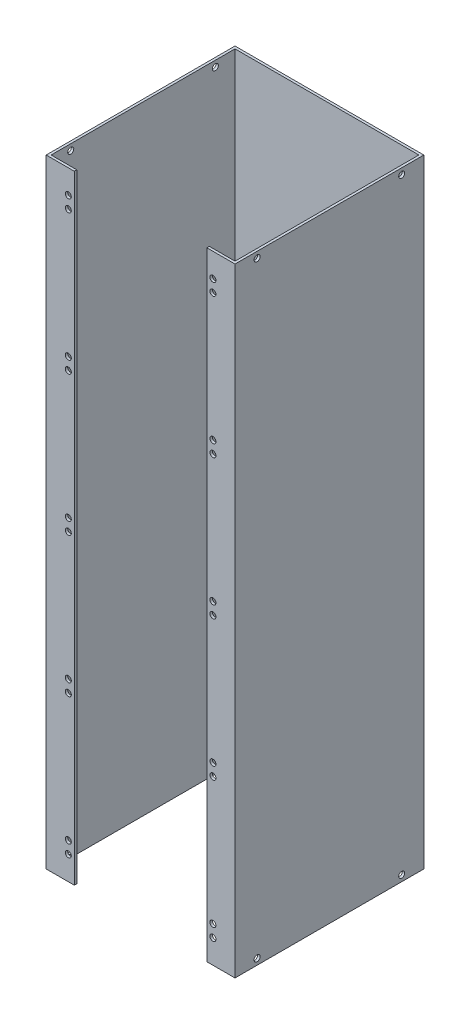
SolidWorks part; units mm, degrees
ref_plane "Front Plane" through (0, 0, 0) normal (0, 0, 1) x (1, 0, 0)
ref_plane "Top Plane" through (0, 0, 0) normal (0, 1, 0) x (1, 0, 0)
ref_plane "Right Plane" through (0, 0, 0) normal (1, 0, 0) x (0, 0, -1)
sketch "Sketch1" plane through (0, 0, 0) normal (0, 1, 0) x (1, 0, 0)
  line L0 (0, 0) -> (14.9, 0)
  line L1 (14.9, 0) -> (14.9, 1.3)
  line L2 (14.9, 1.3) -> (1.3, 1.3)
  line L3 (1.3, 1.3) -> (1.3, 98.7)
  line L4 (1.3, 98.7) -> (98.7, 98.7)
  line L5 (98.7, 98.7) -> (98.7, 1.3)
  line L6 (98.7, 1.3) -> (85.1, 1.3)
  line L7 (85.1, 1.3) -> (85.1, 0)
  line L8 (85.1, 0) -> (100, 0)
  line L9 (100, 0) -> (100, 100)
  line L10 (100, 100) -> (0, 100)
  line L11 (0, 100) -> (0, 0)
  dimension "D1" = 100
  dimension "D2" = 100
  dimension "D3" = 1.3
  dimension "D4" = 1.3
  dimension "D5" = 1.3
  dimension "D6" = 1.3
  dimension "D7" = 1.3
  dimension "D8" = 100
  dimension "D9" = 14.9
  dimension "D10" = 14.9
extrude "Boss-Extrude1" add sketch "Sketch1" along normal blind 327.5 contours L11 L0 L1 L2 L3 L4 L5 L6 L7 L8 L9 L10
sketch "Sketch2" plane through (0, 0, 0) normal (0, 0, 1) x (1, 0, 0)
  line L0 (14.9, 327.5) -> (14.9, 0) construction
  line L1 (0, 327.5) -> (14.9, 327.5) construction
  line L5 (85.1, 327.5) -> (85.1, 0) construction
  circle A0 centre (11.7, 314.9) radius 1.6
  circle A1 centre (11.7, 308.5) radius 1.6
  circle A2 centre (11.7, 240.925) radius 1.6
  circle A3 centre (11.7, 234.525) radius 1.6
  circle A4 centre (11.7, 166.95) radius 1.6
  circle A5 centre (11.7, 160.55) radius 1.6
  circle A6 centre (11.7, 92.975) radius 1.6
  circle A7 centre (11.7, 86.575) radius 1.6
  circle A8 centre (11.7, 19) radius 1.6
  circle A9 centre (11.7, 12.6) radius 1.6
  circle A10 centre (88.3, 314.9) radius 1.6
  circle A11 centre (88.3, 308.5) radius 1.6
  circle A12 centre (88.3, 240.925) radius 1.6
  circle A13 centre (88.3, 234.525) radius 1.6
  circle A14 centre (88.3, 166.95) radius 1.6
  circle A15 centre (88.3, 160.55) radius 1.6
  circle A16 centre (88.3, 19) radius 1.6
  circle A17 centre (88.3, 12.6) radius 1.6
  circle A18 centre (88.3, 86.575) radius 1.6
  circle A19 centre (88.3, 92.975) radius 1.6
  dimension "D1" = 3.2
  dimension "D2" = 3.2
  dimension "D3" = 6.4
  dimension "D4" = 3.2
  dimension "D5" = 12.6
  dimension "D7" = 3.2
  dimension "D6" = 5
extrude "Cut-Extrude1" cut sketch "Sketch2" against normal blind 1.3
sketch "Sketch4" plane through (0, 0, 0) normal (-1, 0, 0) x (0, 0, 1)
  line L0 (-100, 327.5) -> (-100, 0) construction
  line L1 (0, 327.5) -> (0, 0) construction
  line L2 (-100, 327.5) -> (0, 327.5) construction
  line L3 (-100, 0) -> (0, 0) construction
  circle A0 centre (-88.3, 324.3) radius 1.6
  circle A1 centre (-11.7, 324.3) radius 1.6
  circle A2 centre (-88.3, 3.2) radius 1.6
  circle A3 centre (-11.7, 3.2) radius 1.6
  dimension "D1" = 3.2
  dimension "D2" = 3.2
  dimension "D7" = 3.2
  dimension "D8" = 3.2
  dimension "D9" = 11.7
  dimension "D10" = 11.7
  dimension "D3" = 11.7
  dimension "D4" = 11.7
  dimension "D5" = 3.2
  dimension "D6" = 3.2
  dimension "D11" = 3.2
  dimension "D12" = 3.2
extrude "Cut-Extrude2" cut sketch "Sketch4" against normal blind 100
